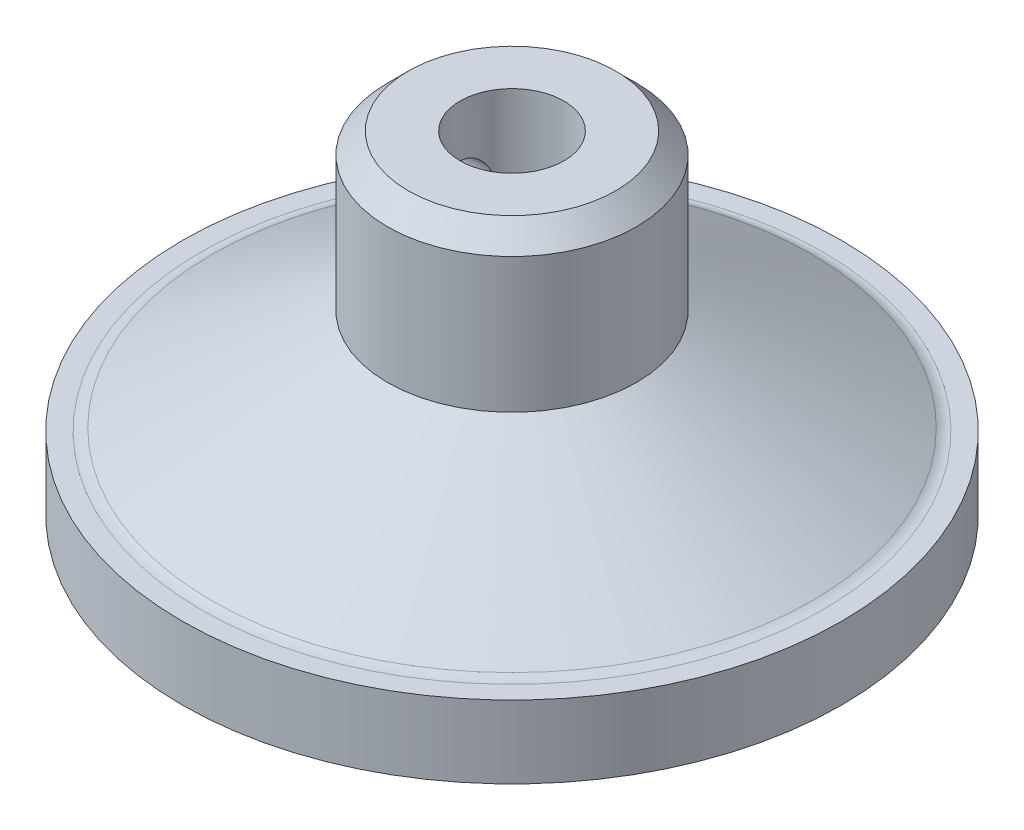
SolidWorks part; units mm, degrees
ref_plane "Front Plane" through (0, 0, 0) normal (0, 0, 1) x (1, 0, 0)
ref_plane "Top Plane" through (0, 0, 0) normal (0, 1, 0) x (1, 0, 0)
ref_plane "Right Plane" through (0, 0, 0) normal (1, 0, 0) x (0, 0, -1)
sketch "Sketch1" plane through (0, 0, 0) normal (0, 0, 1) x (1, 0, 0)
  line L0 (0, 31.9758) -> (0, -31.9758) construction
  line L1 (2.5, 10.999) -> (2.5, 3.5)
  line L2 (5.0622, 0) -> (13.75, -5.0159)
  line L3 (6, 3.5) -> (14.6878, -1.5159)
  line L4 (15.8878, -5.0159) -> (13.75, -5.0159)
  line L6 (5.0622, 0) -> (0, 0)
  line L7 (6, 3.5) -> (6, 10.999)
  line L8 (2.5, 10.999) -> (6, 10.999)
  line L9 (0, 0) -> (0, 3.5)
  line L10 (0, 3.5) -> (2.5, 3.5)
  line L11 (14.6878, -1.5159) -> (15.8878, -1.5159)
  line L12 (15.8878, -1.5159) -> (15.8878, -5.0159)
  point P4 (0, 0)
  dimension "D6" = 3.5
  dimension "D1" = 5
  dimension "D2" = 3.5
  dimension "D3" = 3.5
  dimension "D4" = 150
  dimension "D5" = 27.5
  dimension "D7" = 10.999
  dimension "D8" = 3.5
  dimension "D9" = 1.2
revolve "Revolve1" add sketch "Sketch1" angle 360 about L0
fillet "Fillet1" radius 3 1 edges at (0, -5.0159, 13.75)
sketch "Sketch2" plane through (0, 0, 0) normal (1, 0, 0) x (0, 0, -1)
  line L0 (-6, 10.999) -> (-6, 3.5) construction
  line L1 (-6, 10.999) -> (-6, 3.5) construction
  circle A0 centre (0, 7.2495) radius 1.5
  point P4 (-6, 7.2495)
  dimension "D1" = 3
chamfer "Chamfer1" distance 1 angle 45 1 edges at (0, 10.999, 6)
fillet "Fillet2" radius 1 1 edges at (0, -1.5159, 14.6878)
hole_wizard "M3 Tapped Hole1" positions "3DSketch2" profile "Sketch4" tap size "M3" standard "ISO"
sketch3d "3DSketch2"
  line L3 (0, 7.2495, 0) -> (-6, 7.2495, 0) construction
  point P0 (0, 7.2495, 0)
  point P11 (-6, 7.2495, 0)
  point P19 (-9.1202, 7.2495, 0)
  point P29 (-4.2814, 7.2495, 0)
  point P39 (0, 0, 0)
sketch "Sketch4" plane through (-6, 7.2495, 0) normal (0, 1, 0) x (0, 0, 1)
  line L0 (0, 0) -> (0, 7.2511)
  line L1 (0, 7.2511) -> (1.25, 6.5)
  line L2 (1.25, 6.5) -> (1.25, 0.275)
  line L3 (1.25, 0.275) -> (1.525, 0)
  line L5 (1.525, 0) -> (0, 0)
  line L6 (-1.25, 0.275) -> (-1.525, 0) construction
  line L10 (0, 7.2511) -> (-1.25, 6.5) construction
  line L11 (0, -6.35) -> (0, 107.95) construction
  dimension "Tap Drill Dia." = 2.5
  dimension "Tap Drill Depth" = 6.5
  dimension "Near C'Sink Dia." = 3.05
  dimension "Near C'Sink Angle" = 90
  dimension "Drill Angle" = 118
cosmetic thread "Hole Thread1" parameters "D1"=3.8349, "D2"=3
cosmetic thread "Hole Thread2" parameters "D1"=3.8349, "D2"=3
